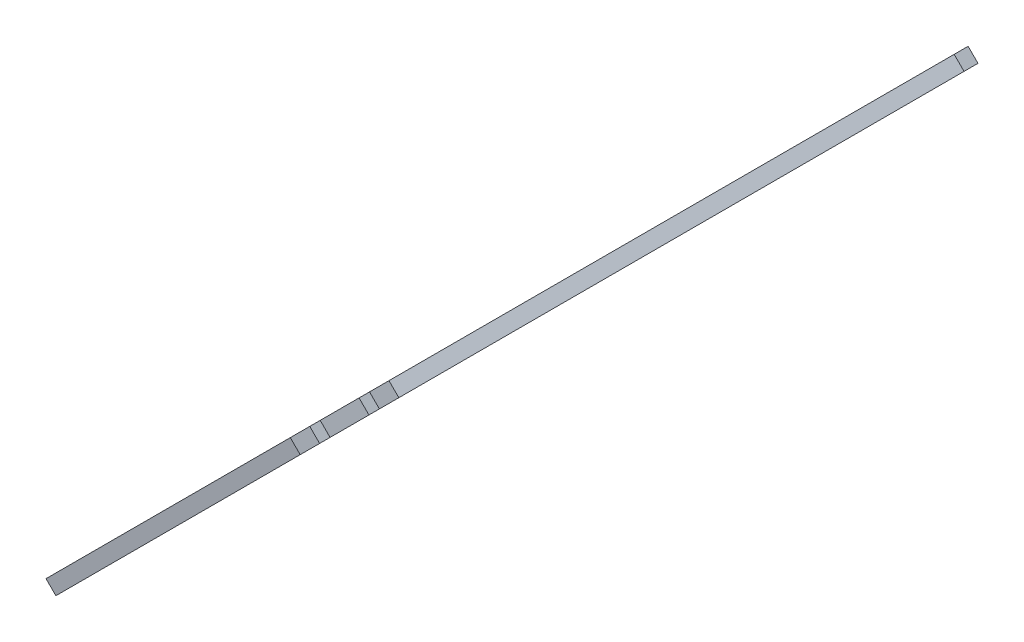
SolidWorks part; units mm, degrees
ref_plane "Front Plane" through (0, 0, 0) normal (0, 0, 1) x (1, 0, 0)
ref_plane "Top Plane" through (0, 0, 0) normal (0, 1, 0) x (1, 0, 0)
ref_plane "Right Plane" through (0, 0, 0) normal (1, 0, 0) x (0, 0, -1)
ref_plane "Plane1" through (164.5, 164.5, 0) normal (-0.7071, -0.7071, 0) x (-0.7071, 0.7071, 0)
sketch "Sketch1" plane through (164.5, 164.5, 0) normal (-0.7071, -0.7071, 0) x (-0.7071, 0.7071, 0)
  line L1 (182.6381, -115) -> (282.6381, -115)
  line L10 (237.9381, -115) -> (282.6381, -115)
  line L11 (227.3381, -52.8) -> (237.9381, -52.8)
  line L18 (227.3381, -52.8) -> (237.9381, -52.8) construction
  line L19 (227.3381, -115) -> (227.3381, -52.8)
  line L20 (182.6381, -115) -> (227.3381, -115)
  line L21 (-227.6381, 0) -> (182.6381, -115)
  line L23 (-227.6381, 10) -> (-227.6381, 0)
  line L24 (692.9144, 10) -> (-227.6381, 10)
  line L25 (692.9144, 0) -> (692.9144, 10)
  line L26 (282.6381, -115) -> (692.9144, 0)
  line L32 (-227.6381, 0) -> (182.6381, -115)
  line L33 (-227.6381, 10) -> (-227.6381, 0)
  line L34 (692.9144, 10) -> (-227.6381, 10)
  line L35 (692.9144, 0) -> (692.9144, 10)
  line L36 (282.6381, -115) -> (692.9144, 0)
  line L46 (227.3381, -115) -> (227.3381, -52.8) construction
  line L47 (237.9381, -52.8) -> (237.9381, -115)
  line L48 (237.9381, -52.8) -> (237.9381, -115) construction
  dimension "D1" = 0
extrude "Boss-Extrude1" add sketch "Sketch1" along normal up to surface (5 mm away) and the other way up to surface (5 mm away)
move or copy body "Body-Move/Copy1" bodies to move or copy 101 copy no rotation origin (0, 329, 0) rotation axis (0, 0, -1) rotation angle 90
ref_plane "Plane2" through (-164.5, 164.5, 0) normal (-0.7071, 0.7071, 0) x (0.6804, 0.6804, 0.2722)
sketch "Sketch2" plane through (-164.5, 164.5, 0) normal (-0.7071, 0.7071, 0) x (0.6804, 0.6804, 0.2722)
  line L0 (216.0346, 71.4961) -> (226.2344, 74.3811)
  line L1 (243.4708, 13.9926) -> (226.2344, 74.3811)
  line L2 (255.1552, -47.3427) -> (221.1345, 72.9386) construction
  line L3 (232.9006, 11.3146) -> (243.3891, 14.2812) construction
  line L5 (232.9822, 11.026) -> (243.4708, 13.9926)
  line L9 (232.9822, 11.026) -> (216.0346, 71.4961)
  line L12 (207.0427, -60.951) -> (303.2677, -33.7344)
  line L13 (303.2677, -33.7344) -> (666.7572, 188.5874)
  line L14 (303.2677, -33.7344) -> (666.7572, 188.5874) construction
  line L15 (-219.0449, -61.9553) -> (207.0427, -60.951)
  line L16 (-219.0449, -61.9553) -> (207.0427, -60.951) construction
  line L17 (-221.7665, -52.3327) -> (-219.0449, -61.9553)
  line L18 (207.0427, -60.951) -> (303.2677, -33.7344) construction
  line L28 (-221.7665, -52.3327) -> (-219.0449, -61.9553) construction
  line L29 (664.0355, 198.2099) -> (-221.7665, -52.3327)
  line L30 (664.0355, 198.2099) -> (-221.7665, -52.3327) construction
  line L31 (666.7572, 188.5874) -> (664.0355, 198.2099)
  line L32 (666.7572, 188.5874) -> (664.0355, 198.2099) construction
  point P11 (238.1448, 12.7979)
  point P16 (221.1345, 72.9386)
  dimension "D2" = 0.3
  dimension "D3" = 10.6
  dimension "D4" = 62.8
  dimension "D1" = 0
extrude "Cut-Extrude2" cut sketch "Sketch2" against normal through all both and the other way through all
ref_plane "Plane3" through (0, 0, 115) normal (0, 0, 1) x (1, 0, 0)
sketch "Sketch3" plane through (0, 0, 115) normal (0, 0, 1) x (1, 0, 0)
  line L0 (-3.5355, 332.5355) -> (3.5355, 325.4645) construction
  line L1 (-21.2132, 314.8579) -> (-14.1421, 307.7868) construction
  line L2 (14.1421, 350.2132) -> (21.2132, 343.1421) construction
  line L8 (38.8909, 360.8198) -> (31.8198, 367.8909) construction
  line L15 (-24.9609, 311.1102) -> (-17.8898, 304.0391)
  line L16 (10.3945, 346.4655) -> (17.4655, 339.3945)
  line L17 (-17.4655, 318.6055) -> (-10.3945, 311.5345)
  line L18 (17.8898, 353.9609) -> (24.9609, 346.8898)
  line L19 (-24.9609, 311.1102) -> (-17.4655, 318.6055)
  line L20 (-17.8898, 304.0391) -> (-10.3945, 311.5345)
  line L21 (10.3945, 346.4655) -> (17.8898, 353.9609)
  line L22 (17.4655, 339.3945) -> (24.9609, 346.8898)
  dimension "D2" = 25
  dimension "D3" = 25
  dimension "D4" = 5.3
  dimension "D5" = 5.3
extrude "Cut-Extrude3" cut sketch "Sketch3" against normal blind 30.3
